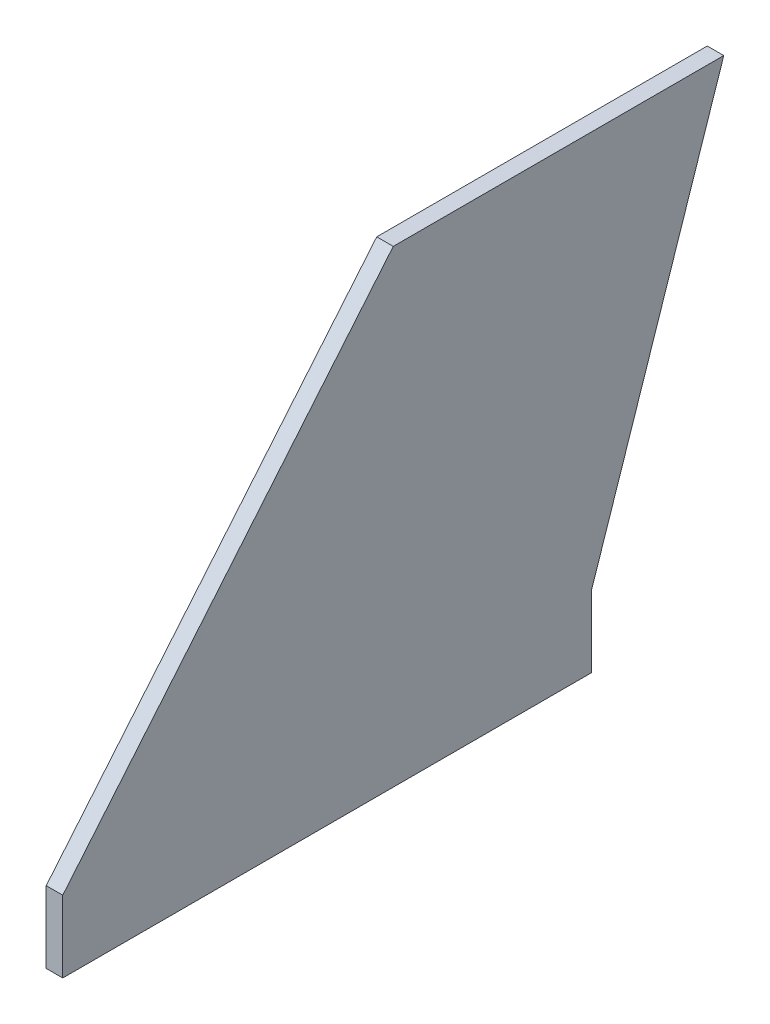
SolidWorks part; units mm, degrees
ref_plane "Plan de face" through (0, 0, 0) normal (0, 0, 1) x (1, 0, 0)
ref_plane "Plan de dessus" through (0, 0, 0) normal (0, 1, 0) x (1, 0, 0)
ref_plane "Plan de droite" through (0, 0, 0) normal (1, 0, 0) x (0, 0, -1)
sketch "Esquisse2" plane through (0, 0, 0) normal (1, 0, 0) x (0, 0, -1)
  line L0 (0, 0) -> (-203.2, 0)
  line L1 (-203.2, 0) -> (-203.2, -27.559)
  line L2 (-203.2, -27.559) -> (0, -27.559)
  line L3 (0, -27.559) -> (0, 0)
  line L4 (-203.2, 0) -> (-76.2, 152.4)
  line L5 (-76.2, 152.4) -> (50.8, 152.4)
  line L6 (50.8, 152.4) -> (0, 0)
  dimension "D1" = 27.559
  dimension "D2" = 152.4
  dimension "D3" = 203.2
  dimension "D4" = 127
  dimension "D5" = 50.8
extrude "Boss.-Extru.1" add sketch "Esquisse2" along normal blind 6.35
